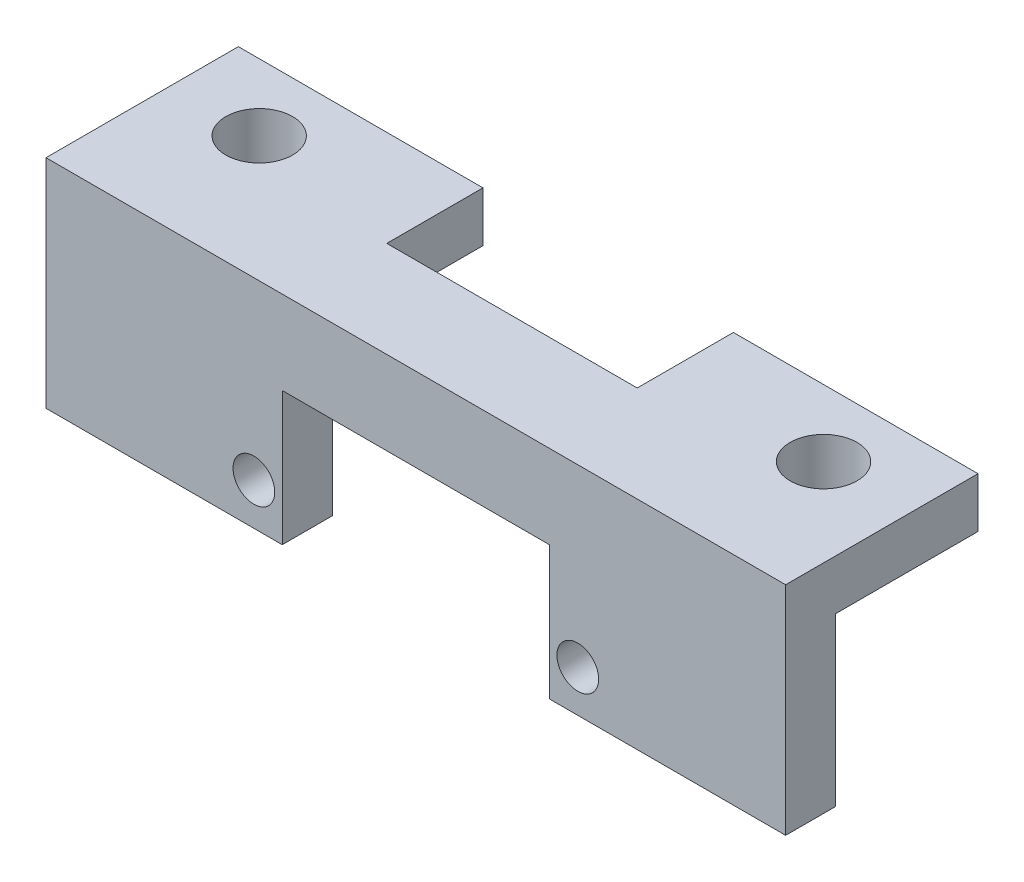
SolidWorks part; units mm, degrees
ref_plane "Plano frontal" through (0, 0, 0) normal (0, 0, 1) x (1, 0, 0)
ref_plane "Plano superior" through (0, 0, 0) normal (0, 1, 0) x (1, 0, 0)
ref_plane "Plano direito" through (0, 0, 0) normal (1, 0, 0) x (0, 0, -1)
sketch "Esboço1" plane through (0, 0, 0) normal (0, 1, 0) x (1, 0, 0)
  line L0 (0, -55) -> (0, 55) construction
  line L1 (22.15, 5.76) -> (7.5, 5.76)
  line L2 (22.15, 5.76) -> (22.15, -5.76)
  line L3 (22.15, -5.76) -> (-22.15, -5.76)
  line L4 (-22.15, 5.76) -> (-22.15, -5.76)
  line L5 (22.15, 5.76) -> (-22.15, -5.76) construction
  line L6 (22.15, -5.76) -> (-22.15, 5.76) construction
  line L7 (-7.5, 5.76) -> (-22.15, 5.76)
  line L9 (-7.5, 5.76) -> (-7.5, 0)
  line L10 (-7.5, 0) -> (7.5, 0)
  line L11 (7.5, 5.76) -> (7.5, 0)
  circle A0 centre (-16.9, 1.76) radius 2
  circle A1 centre (16.9, 1.76) radius 2
  point P0 (0, 0)
  point P16 (0, 0)
  dimension "D5" = 4
  dimension "D1" = 44.3
  dimension "D2" = 11.52
  dimension "D3" = 4
  dimension "D4" = 5.25
  dimension "D6" = 15
extrude "Ressalto-extrusão1" add sketch "Esboço1" along normal blind 3
sketch "Esboço2" plane through (0, 0, 0) normal (0, -1, 0) x (-1, 0, 0)
  line L0 (-22.15, -5.76) -> (-22.15, 5.76) construction
  line L1 (22.15, -5.76) -> (-22.15, -5.76)
  line L2 (22.15, -5.76) -> (22.15, -2.76)
  line L3 (22.15, -2.76) -> (-22.15, -2.76)
  line L4 (-22.15, -5.76) -> (-22.15, -2.76)
  dimension "D1" = 3
extrude "Ressalto-extrusão2" add sketch "Esboço2" along normal blind 10
sketch "Esboço3" plane through (0, 0, 5.76) normal (0, 0, 1) x (1, 0, 0)
  line L0 (22.15, -10) -> (-22.15, -10) construction
  line L1 (-8, -2) -> (8, -2)
  line L2 (-8, -2) -> (-8, -10)
  line L3 (-8, -10) -> (8, -10)
  line L4 (8, -2) -> (8, -10)
  line L5 (0, -6.336) -> (0, 6.336) construction
  line L6 (-22.15, 3) -> (22.15, 3) construction
  circle A0 centre (-9.7, -7.5) radius 1.25
  circle A1 centre (9.7, -7.5) radius 1.25
  point P6 (0, -2)
  dimension "D4" = 2.5
  dimension "D1" = 16
  dimension "D2" = 5
  dimension "D3" = 1.7
  dimension "D5" = 5.5
extrude "Corte-extrusão1" cut sketch "Esboço3" against normal up to surface (3 mm away) up to face at (0, -5, 2.76)
